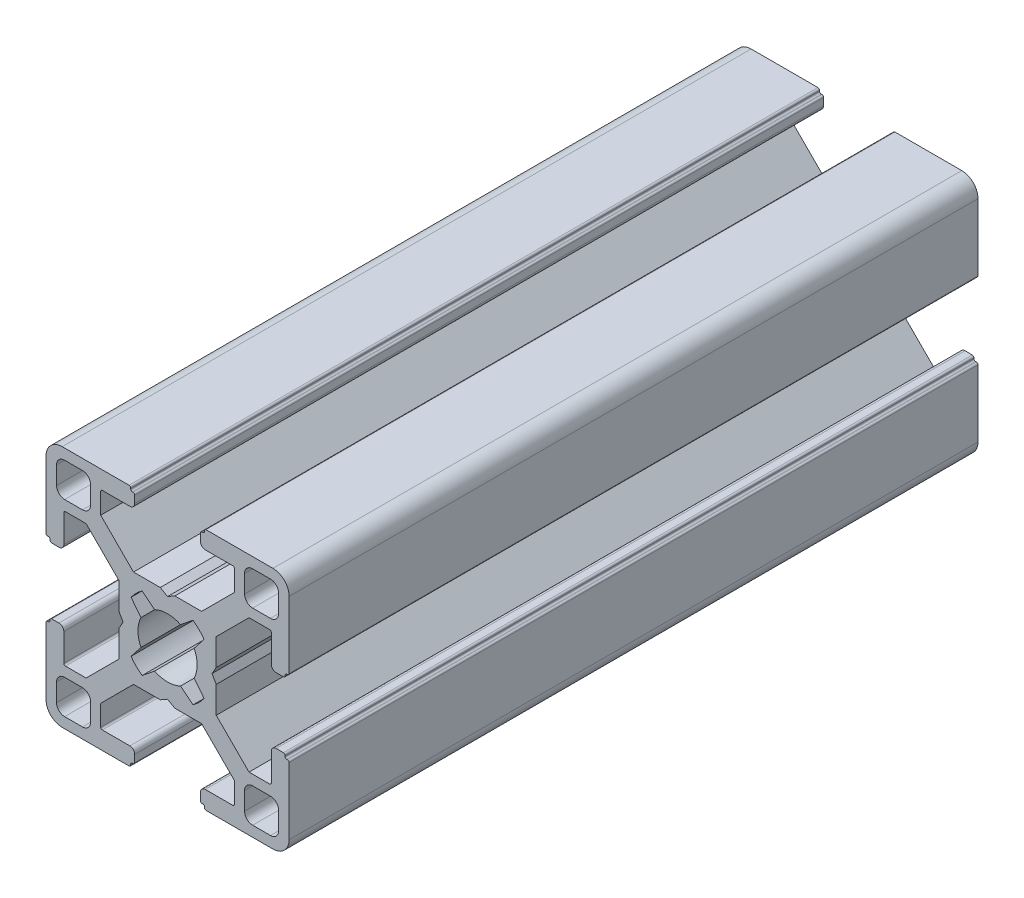
SolidWorks part; units mm, degrees
material "1060 Alloy"
ref_plane "Front" through (0, 0, 0) normal (0, 0, 1) x (1, 0, 0)
ref_plane "Top" through (0, 0, 0) normal (0, 1, 0) x (1, 0, 0)
ref_plane "Right" through (0, 0, 0) normal (1, 0, 0) x (0, 0, -1)
ref_plane "Plane1" through (0, 0, 25) normal (0, 0, 1) x (1, 0, 0)
sketch "Sketch1" plane through (0, 0, 25) normal (0, 0, 1) x (1, 0, 0)
  line L0 (-12.7, 13.7) -> (-10.5, 13.7)
  line L1 (-9.5, 12.7) -> (-9.5, 10.5)
  line L2 (-10.5, 9.5) -> (-12.7, 9.5)
  line L3 (-13.7, 10.5) -> (-13.7, 12.7)
  line L4 (-10.5, -13.7) -> (-12.7, -13.7)
  line L5 (-13.7, -12.7) -> (-13.7, -10.5)
  line L6 (-12.7, -9.5) -> (-10.5, -9.5)
  line L7 (-9.5, -10.5) -> (-9.5, -12.7)
  line L8 (10.5, 13.7) -> (12.7, 13.7)
  line L9 (13.7, 12.7) -> (13.7, 10.5)
  line L10 (12.7, 9.5) -> (10.5, 9.5)
  line L11 (9.5, 10.5) -> (9.5, 12.7)
  line L12 (13.7, -10.5) -> (13.7, -12.7)
  line L13 (12.7, -13.7) -> (10.5, -13.7)
  line L14 (9.5, -12.7) -> (9.5, -10.5)
  line L15 (10.5, -9.5) -> (12.7, -9.5)
  line L16 (-3.1359, 4.5184) -> (-1.6001, 3.2806)
  line L17 (1.6001, 3.2806) -> (3.1359, 4.5184)
  line L18 (4.5053, 3.1547) -> (3.2806, 1.6001)
  line L19 (3.2806, -1.6001) -> (4.5053, -3.1547)
  line L20 (3.1359, -4.5184) -> (1.6001, -3.2806)
  line L21 (-1.6001, -3.2806) -> (-3.1359, -4.5184)
  line L22 (-4.5053, -3.1547) -> (-3.2806, -1.6001)
  line L23 (-3.2806, 1.6001) -> (-4.5053, 3.1547)
  line L24 (-4.05, 13.4) -> (-4.05, 14.3)
  line L25 (-4.25, 14.5) -> (-4.35, 14.5)
  line L26 (-4.55, 14.7) -> (-4.55, 14.8)
  line L27 (-4.75, 15) -> (-13, 15)
  line L28 (-15, 13) -> (-15, 4.75)
  line L29 (-14.8, 4.55) -> (-14.7, 4.55)
  line L30 (-14.5, 4.35) -> (-14.5, 4.25)
  line L31 (-14.3, 4.05) -> (-13.4, 4.05)
  line L32 (-12.8, 4.65) -> (-12.8, 8.05)
  line L33 (-12.6, 8.25) -> (-10.05, 8.25)
  line L34 (-10.05, 8.25) -> (-6.0045, 4.2045)
  line L35 (-6.0045, 4.2045) -> (-6.0045, 0.9)
  line L36 (-6.0045, 0.9) -> (-5.4849, 0)
  line L37 (-5.4849, 0) -> (-6.0045, -0.9)
  line L38 (-6.0045, -0.9) -> (-6.0045, -4.2045)
  line L39 (-6.0045, -4.2045) -> (-10.05, -8.25)
  line L40 (-10.05, -8.25) -> (-12.6, -8.25)
  line L41 (-12.8, -8.05) -> (-12.8, -4.65)
  line L42 (-13.4, -4.05) -> (-14.3, -4.05)
  line L43 (-14.5, -4.25) -> (-14.5, -4.35)
  line L44 (-14.7, -4.55) -> (-14.8, -4.55)
  line L45 (-15, -4.75) -> (-15, -13)
  line L46 (-13, -15) -> (-4.75, -15)
  line L47 (-4.55, -14.8) -> (-4.55, -14.7)
  line L48 (-4.35, -14.5) -> (-4.25, -14.5)
  line L49 (-4.05, -14.3) -> (-4.05, -13.4)
  line L50 (-4.65, -12.8) -> (-8.05, -12.8)
  line L51 (-8.25, -12.6) -> (-8.25, -10.05)
  line L52 (-8.25, -10.05) -> (-4.2045, -6)
  line L53 (-4.2045, -6) -> (-0.9, -6)
  line L54 (-0.9, -6) -> (0, -5.4849)
  line L55 (0, -5.4849) -> (0.9, -6)
  line L56 (0.9, -6) -> (4.2045, -6)
  line L57 (4.2045, -6) -> (8.25, -10.05)
  line L58 (8.25, -10.05) -> (8.25, -12.6)
  line L59 (8.05, -12.8) -> (4.65, -12.8)
  line L60 (4.05, -13.4) -> (4.05, -14.3)
  line L61 (4.25, -14.5) -> (4.35, -14.5)
  line L62 (4.55, -14.7) -> (4.55, -14.8)
  line L63 (4.75, -15) -> (13, -15)
  line L64 (15, -13) -> (15, -4.75)
  line L65 (14.8, -4.55) -> (14.7, -4.55)
  line L66 (14.5, -4.35) -> (14.5, -4.25)
  line L67 (14.3, -4.05) -> (13.4, -4.05)
  line L68 (12.8, -4.65) -> (12.8, -8.05)
  line L69 (12.6, -8.25) -> (10.05, -8.25)
  line L70 (10.05, -8.25) -> (6.0045, -4.2045)
  line L71 (6.0045, -4.2045) -> (6.0045, -0.9)
  line L72 (6.0045, -0.9) -> (5.4849, 0)
  line L73 (5.4849, 0) -> (6.0045, 0.9)
  line L74 (6.0045, 0.9) -> (6.0045, 4.2045)
  line L75 (6.0045, 4.2045) -> (10.05, 8.25)
  line L76 (10.05, 8.25) -> (12.6, 8.25)
  line L77 (12.8, 8.05) -> (12.8, 4.65)
  line L78 (13.4, 4.05) -> (14.3, 4.05)
  line L79 (14.5, 4.25) -> (14.5, 4.35)
  line L80 (14.7, 4.55) -> (14.8, 4.55)
  line L81 (15, 4.75) -> (15, 13)
  line L82 (13, 15) -> (4.75, 15)
  line L83 (4.55, 14.8) -> (4.55, 14.7)
  line L84 (4.35, 14.5) -> (4.25, 14.5)
  line L85 (4.05, 14.3) -> (4.05, 13.4)
  line L86 (4.65, 12.8) -> (8.05, 12.8)
  line L87 (8.25, 12.6) -> (8.25, 10.05)
  line L88 (8.25, 10.05) -> (4.2045, 6)
  line L89 (4.2045, 6) -> (0.9, 6)
  line L90 (0.9, 6) -> (0, 5.4849)
  line L91 (0, 5.4849) -> (-0.9, 6)
  line L92 (-0.9, 6) -> (-4.2045, 6)
  line L93 (-4.2045, 6) -> (-8.25, 10.05)
  line L94 (-8.25, 10.05) -> (-8.25, 12.6)
  line L95 (-8.05, 12.8) -> (-4.65, 12.8)
  arc A0 (-13.7, 12.7) -> (-12.7, 13.7) centre (-12.7, 12.7) cw
  arc A1 (-10.5, 13.7) -> (-9.5, 12.7) centre (-10.5, 12.7) cw
  arc A2 (-9.5, 10.5) -> (-10.5, 9.5) centre (-10.5, 10.5) cw
  arc A3 (-12.7, 9.5) -> (-13.7, 10.5) centre (-12.7, 10.5) cw
  arc A4 (-9.5, -12.7) -> (-10.5, -13.7) centre (-10.5, -12.7) cw
  arc A5 (-12.7, -13.7) -> (-13.7, -12.7) centre (-12.7, -12.7) cw
  arc A6 (-13.7, -10.5) -> (-12.7, -9.5) centre (-12.7, -10.5) cw
  arc A7 (-10.5, -9.5) -> (-9.5, -10.5) centre (-10.5, -10.5) cw
  arc A8 (9.5, 12.7) -> (10.5, 13.7) centre (10.5, 12.7) cw
  arc A9 (12.7, 13.7) -> (13.7, 12.7) centre (12.7, 12.7) cw
  arc A10 (13.7, 10.5) -> (12.7, 9.5) centre (12.7, 10.5) cw
  arc A11 (10.5, 9.5) -> (9.5, 10.5) centre (10.5, 10.5) cw
  arc A12 (13.7, -12.7) -> (12.7, -13.7) centre (12.7, -12.7) cw
  arc A13 (10.5, -13.7) -> (9.5, -12.7) centre (10.5, -12.7) cw
  arc A14 (9.5, -10.5) -> (10.5, -9.5) centre (10.5, -10.5) cw
  arc A15 (12.7, -9.5) -> (13.7, -10.5) centre (12.7, -10.5) cw
  arc A16 (-4.5053, 3.1547) -> (-3.1359, 4.5184) centre (0, 0) cw
  arc A17 (-1.6001, 3.2806) -> (1.6001, 3.2806) centre (0, 0) cw
  arc A18 (3.1359, 4.5184) -> (4.5053, 3.1547) centre (0, 0) cw
  arc A19 (3.2806, 1.6001) -> (3.2806, -1.6001) centre (0, 0) cw
  arc A20 (4.5053, -3.1547) -> (3.1359, -4.5184) centre (0, 0) cw
  arc A21 (1.6001, -3.2806) -> (-1.6001, -3.2806) centre (0, 0) cw
  arc A22 (-3.1359, -4.5184) -> (-4.5053, -3.1547) centre (0, 0) cw
  arc A23 (-3.2806, -1.6001) -> (-3.2806, 1.6001) centre (0, 0) cw
  arc A24 (-4.65, 12.8) -> (-4.05, 13.4) centre (-4.65, 13.4) ccw
  arc A25 (-4.05, 14.3) -> (-4.25, 14.5) centre (-4.25, 14.3) ccw
  arc A26 (-4.35, 14.5) -> (-4.55, 14.7) centre (-4.35, 14.7) cw
  arc A27 (-4.55, 14.8) -> (-4.75, 15) centre (-4.75, 14.8) ccw
  arc A28 (-13, 15) -> (-15, 13) centre (-13, 13) ccw
  arc A29 (-15, 4.75) -> (-14.8, 4.55) centre (-14.8, 4.75) ccw
  arc A30 (-14.7, 4.55) -> (-14.5, 4.35) centre (-14.7, 4.35) cw
  arc A31 (-14.5, 4.25) -> (-14.3, 4.05) centre (-14.3, 4.25) ccw
  arc A32 (-13.4, 4.05) -> (-12.8, 4.65) centre (-13.4, 4.65) ccw
  arc A33 (-12.8, 8.05) -> (-12.6, 8.25) centre (-12.6, 8.05) cw
  arc A34 (-12.6, -8.25) -> (-12.8, -8.05) centre (-12.6, -8.05) cw
  arc A35 (-12.8, -4.65) -> (-13.4, -4.05) centre (-13.4, -4.65) ccw
  arc A36 (-14.3, -4.05) -> (-14.5, -4.25) centre (-14.3, -4.25) ccw
  arc A37 (-14.5, -4.35) -> (-14.7, -4.55) centre (-14.7, -4.35) cw
  arc A38 (-14.8, -4.55) -> (-15, -4.75) centre (-14.8, -4.75) ccw
  arc A39 (-15, -13) -> (-13, -15) centre (-13, -13) ccw
  arc A40 (-4.75, -15) -> (-4.55, -14.8) centre (-4.75, -14.8) ccw
  arc A41 (-4.55, -14.7) -> (-4.35, -14.5) centre (-4.35, -14.7) cw
  arc A42 (-4.25, -14.5) -> (-4.05, -14.3) centre (-4.25, -14.3) ccw
  arc A43 (-4.05, -13.4) -> (-4.65, -12.8) centre (-4.65, -13.4) ccw
  arc A44 (-8.05, -12.8) -> (-8.25, -12.6) centre (-8.05, -12.6) cw
  arc A45 (8.25, -12.6) -> (8.05, -12.8) centre (8.05, -12.6) cw
  arc A46 (4.65, -12.8) -> (4.05, -13.4) centre (4.65, -13.4) ccw
  arc A47 (4.05, -14.3) -> (4.25, -14.5) centre (4.25, -14.3) ccw
  arc A48 (4.35, -14.5) -> (4.55, -14.7) centre (4.35, -14.7) cw
  arc A49 (4.55, -14.8) -> (4.75, -15) centre (4.75, -14.8) ccw
  arc A50 (13, -15) -> (15, -13) centre (13, -13) ccw
  arc A51 (15, -4.75) -> (14.8, -4.55) centre (14.8, -4.75) ccw
  arc A52 (14.7, -4.55) -> (14.5, -4.35) centre (14.7, -4.35) cw
  arc A53 (14.5, -4.25) -> (14.3, -4.05) centre (14.3, -4.25) ccw
  arc A54 (13.4, -4.05) -> (12.8, -4.65) centre (13.4, -4.65) ccw
  arc A55 (12.8, -8.05) -> (12.6, -8.25) centre (12.6, -8.05) cw
  arc A56 (12.6, 8.25) -> (12.8, 8.05) centre (12.6, 8.05) cw
  arc A57 (12.8, 4.65) -> (13.4, 4.05) centre (13.4, 4.65) ccw
  arc A58 (14.3, 4.05) -> (14.5, 4.25) centre (14.3, 4.25) ccw
  arc A59 (14.5, 4.35) -> (14.7, 4.55) centre (14.7, 4.35) cw
  arc A60 (14.8, 4.55) -> (15, 4.75) centre (14.8, 4.75) ccw
  arc A61 (15, 13) -> (13, 15) centre (13, 13) ccw
  arc A62 (4.75, 15) -> (4.55, 14.8) centre (4.75, 14.8) ccw
  arc A63 (4.55, 14.7) -> (4.35, 14.5) centre (4.35, 14.7) cw
  arc A64 (4.25, 14.5) -> (4.05, 14.3) centre (4.25, 14.3) ccw
  arc A65 (4.05, 13.4) -> (4.65, 12.8) centre (4.65, 13.4) ccw
  arc A66 (8.05, 12.8) -> (8.25, 12.6) centre (8.05, 12.6) cw
  arc A67 (-8.25, 12.6) -> (-8.05, 12.8) centre (-8.05, 12.6) cw
extrude "Boss-Extrude1" add sketch "Sketch1" against normal blind 85
